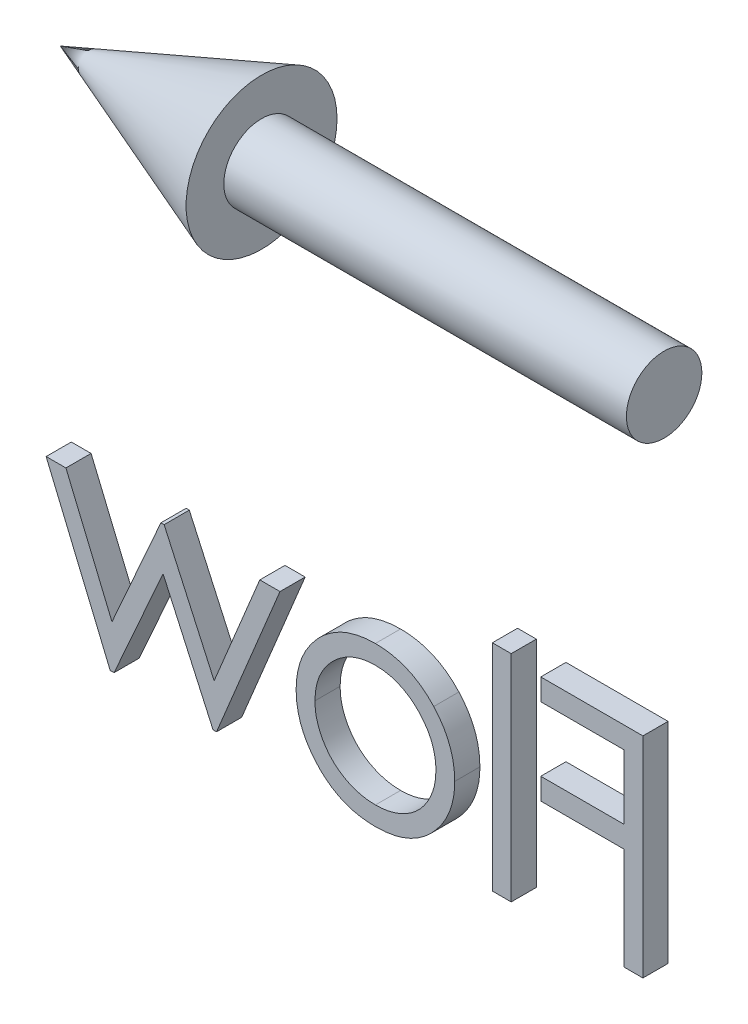
SolidWorks part; units mm, degrees
material "Plain Carbon Steel"
ref_plane "Front Plane" through (0, 0, 0) normal (0, 0, 1) x (1, 0, 0)
ref_plane "Top Plane" through (0, 0, 0) normal (0, 1, 0) x (1, 0, 0)
ref_plane "Right Plane" through (0, 0, 0) normal (1, 0, 0) x (0, 0, -1)
sketch "Sketch1" plane through (0, 0, 0) normal (0, 1, 0) x (1, 0, 0)
  line L0 (0, 0) -> (0, 9.525)
  line L1 (0, 9.525) -> (-101.6, 9.525)
  line L2 (-101.6, 9.525) -> (-101.6, 19.05)
  line L3 (-101.6, 19.05) -> (-152.4, 0)
  line L4 (-152.4, 0) -> (0, 0)
  line L5 (0, 0) -> (-192.0035, 0) construction
  dimension "D1" = 9.525
  dimension "D2" = 19.05
  dimension "D3" = 152.4
  dimension "D4" = 50.8
revolve "Revolve1" add sketch "Sketch1" angle 360 about L5
sketch "Sketch2" plane through (0, 0, 0) normal (0, 0, 1) x (1, 0, 0)
  line L0 (-172.1792, -127) -> (23.3167, -127) construction
  line L1 (-152.4, 0) -> (3.5374, 0) construction
  text T0 "Flow" font "Century Gothic" height in points 200
  point P6 (-74.4313, 0)
  point P8 (-74.4313, -127)
  dimension "D1" = 127
extrude "Boss-Extrude1" add sketch "Sketch2" along normal mid plane 6.35 separate body
